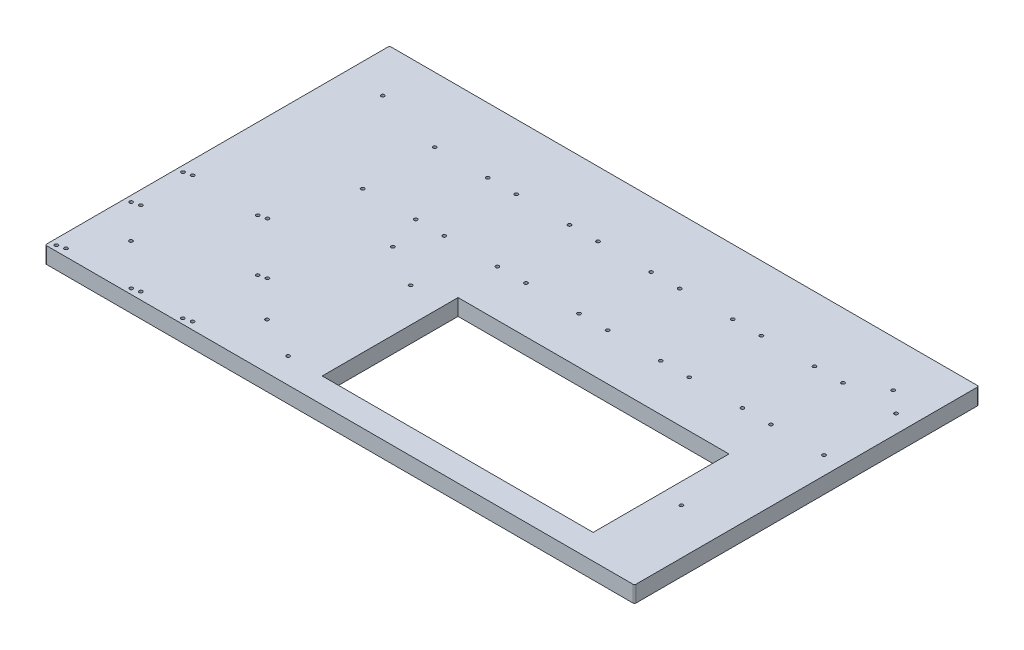
SolidWorks part; units mm, degrees
ref_plane "Front Plane" through (0, 0, 0) normal (0, 0, 1) x (1, 0, 0)
ref_plane "Top Plane" through (0, 0, 0) normal (0, 1, 0) x (1, 0, 0)
ref_plane "Right Plane" through (0, 0, 0) normal (1, 0, 0) x (0, 0, -1)
sketch "Sketch1" plane through (0, 0, 0) normal (0, 1, 0) x (1, 0, 0)
  line L1 (216.5, -126.5) -> (-216.5, -126.5)
  line L2 (216.5, -126.5) -> (216.5, 126.5)
  line L3 (216.5, 126.5) -> (-216.5, 126.5)
  line L4 (-216.5, -126.5) -> (-216.5, 126.5)
  line L5 (216.5, -126.5) -> (-216.5, 126.5) construction
  line L6 (216.5, 126.5) -> (-216.5, -126.5) construction
  point P0 (0, 0)
  dimension "D1" = 433
  dimension "D2" = 253
extrude "Boss-Extrude1" add sketch "Sketch1" along normal blind 12
sketch "Sketch2" plane through (0, 12, 0) normal (0, 1, 0) x (1, 0, 0)
  circle A2 centre (-212.1628, -122.6182) radius 1.25
  circle A4 centre (-212.1628, -29.6182) radius 1.25
  circle A6 centre (-157.1628, -29.6182) radius 1.25
  circle A8 centre (-157.1628, -122.6182) radius 1.25
  circle A9 centre (104.4201, 25.8126) radius 1.25
  circle A10 centre (164.4201, 25.8126) radius 1.25
  circle A11 centre (143.4201, 78.8126) radius 1.25
  circle A12 centre (203.4201, 78.8126) radius 1.25
  circle A13 centre (104.4201, 78.8126) radius 1.25
  circle A14 centre (164.4201, 78.8126) radius 1.25
  circle A15 centre (143.4201, 25.8126) radius 1.25
  circle A16 centre (203.4201, 25.8126) radius 1.25
  circle A32 centre (-206.6382, -121.1) radius 1.25
  circle A33 centre (-206.6382, -28.1) radius 1.25
  circle A34 centre (-151.6382, -28.1) radius 1.25
  circle A35 centre (-151.6382, -121.1) radius 1.25
  circle A36 centre (-119.1712, -122.6857) radius 1.25
  circle A38 centre (-212.1712, -67.6857) radius 1.25
  circle A39 centre (-119.1712, -67.6857) radius 1.25
  circle A40 centre (-113.5762, -121.0961) radius 1.25
  circle A41 centre (44.4201, 25.8126) radius 1.25
  circle A42 centre (-206.5762, -66.0961) radius 1.25
  circle A43 centre (-113.5762, -66.0961) radius 1.25
  circle A44 centre (83.4201, 78.8126) radius 1.25
  circle A45 centre (44.4201, 78.8126) radius 1.25
  circle A46 centre (83.4201, 25.8126) radius 1.25
  circle A47 centre (-15.5799, 25.8126) radius 1.25
  circle A48 centre (23.4201, 78.8126) radius 1.25
  circle A49 centre (-15.5799, 78.8126) radius 1.25
  circle A50 centre (23.4201, 25.8126) radius 1.25
  circle A51 centre (-75.5799, 25.8126) radius 1.25
  circle A52 centre (-36.5799, 78.8126) radius 1.25
  circle A53 centre (-75.5799, 78.8126) radius 1.25
  circle A54 centre (-36.5799, 25.8126) radius 1.25
  circle A55 centre (-135.5799, 25.8126) radius 1.25
  circle A56 centre (-96.5799, 78.8126) radius 1.25
  circle A57 centre (-135.5799, 78.8126) radius 1.25
  circle A58 centre (-96.5799, 25.8126) radius 1.25
  dimension "D1" = 2.5
  dimension "D3" = 2.5
  dimension "D4" = 2.5
  dimension "D2" = 2.5
extrude "Cut-Extrude1" cut sketch "Sketch2" against normal through all
sketch "Sketch3" plane through (0, 12, 0) normal (0, 1, 0) x (1, 0, 0)
  arc A0 (181, -58.5) -> (185, -58.5) centre (183, -58.5) ccw construction
  arc A1 (185, -58.5) -> (181, -58.5) centre (183, -58.5) ccw construction
  arc A2 (-58.5, -108) -> (-54.5, -108) centre (-56.5, -108) ccw construction
  arc A3 (-54.5, -108) -> (-58.5, -108) centre (-56.5, -108) ccw construction
  arc A4 (-56.5, -16) -> (-56.5, -20) centre (-56.5, -18) ccw construction
  arc A5 (-56.5, -20) -> (-56.5, -16) centre (-56.5, -18) ccw construction
  arc A6 (181, -58.5) -> (185, -58.5) centre (183, -58.5) ccw construction
  arc A7 (185, -58.5) -> (181, -58.5) centre (183, -58.5) ccw construction
  arc A8 (-58.5, -108) -> (-54.5, -108) centre (-56.5, -108) ccw construction
  arc A9 (-54.5, -108) -> (-58.5, -108) centre (-56.5, -108) ccw construction
  arc A10 (-56.5, -16) -> (-56.5, -20) centre (-56.5, -18) ccw construction
  arc A11 (-56.5, -20) -> (-56.5, -16) centre (-56.5, -18) ccw construction
  circle A12 centre (-56.5, -18) radius 1.25
  circle A13 centre (-56.5, -108) radius 1.25
  circle A14 centre (183, -58.5) radius 1.25
  dimension "D1" = 2.5
extrude "Cut-Extrude2" cut sketch "Sketch3" against normal blind 15
fillet "Fillet1" radius 1 4 edges at (216.5, 6, -126.5) (216.5, 6, 126.5) (-216.5, 6, 126.5) (-216.5, 6, -126.5)
sketch "Sketch4" plane through (0, 12, 0) normal (0, 1, 0) x (1, 0, 0)
  line L1 (-31.2853, -8.352) -> (167.7879, -8.352)
  line L2 (-31.2853, -8.352) -> (-31.2853, -108.1472)
  line L3 (-31.2853, -108.1472) -> (167.7879, -108.1472)
  line L4 (167.7879, -8.352) -> (167.7879, -108.1472)
extrude "Cut-Extrude3" cut sketch "Sketch4" against normal blind 15
sketch "Sketch5" plane through (0, 0, 0) normal (0, -1, 0) x (1, 0, 0)
  circle A5 centre (-87.5, 0) radius 1.25
  circle A6 centre (187.5, -92.5) radius 1.25
  circle A7 centre (-87.5, 92.5) radius 1.25
  circle A8 centre (-187.5, 92.5) radius 1.25
  circle A9 centre (-187.5, -92.5) radius 1.25
  dimension "D1" = 2.5
extrude "Cut-Extrude4" cut sketch "Sketch5" against normal through all
